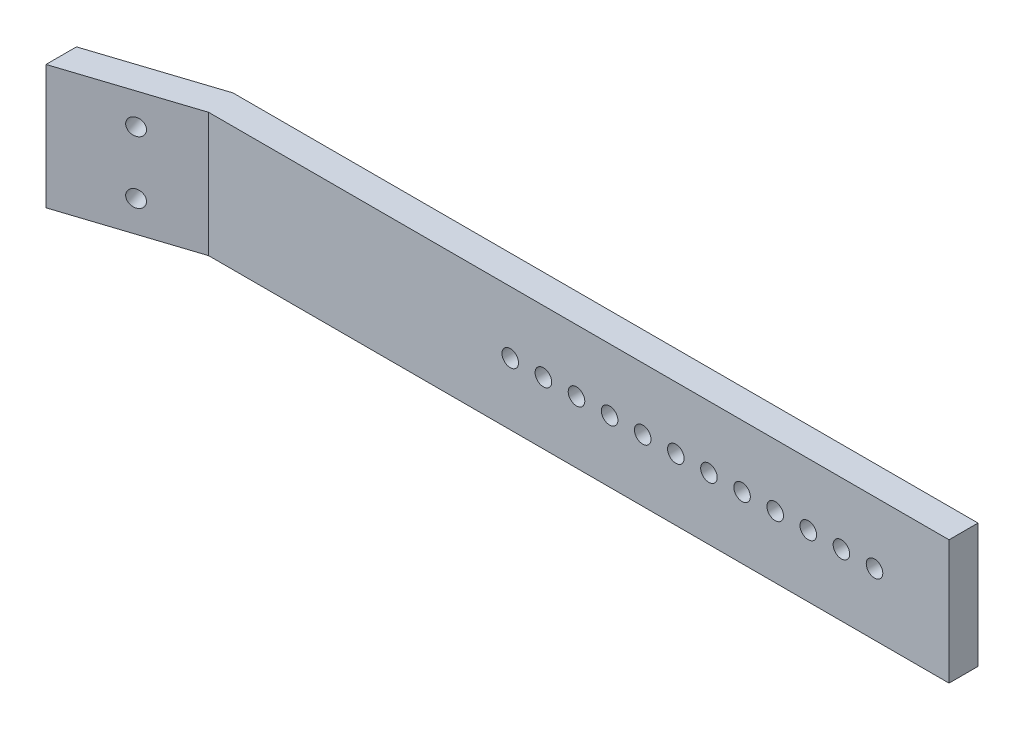
SolidWorks part; units mm, degrees
ref_plane "Front Plane" through (0, 0, 0) normal (0, 0, 1) x (1, 0, 0)
ref_plane "Top Plane" through (0, 0, 0) normal (0, 1, 0) x (1, 0, 0)
ref_plane "Right Plane" through (0, 0, 0) normal (1, 0, 0) x (0, 0, -1)
sketch "Sketch1" plane through (0, 0, 0) normal (0, 0, 1) x (1, 0, 0)
  line L1 (-115, 15) -> (115, 15)
  line L2 (-115, 15) -> (-115, -15)
  line L3 (-115, -15) -> (115, -15)
  line L4 (115, 15) -> (115, -15)
  line L5 (-115, 15) -> (115, -15) construction
  line L6 (-115, -15) -> (115, 15) construction
  point P0 (0, 0)
  dimension "D1" = 30
  dimension "D2" = 230
extrude "Boss-Extrude1" add sketch "Sketch1" along normal blind 50
sketch "Sketch2" plane through (0, -15, 0) normal (0, -1, 0) x (1, 0, 0)
  line L0 (-115, 9.2705) -> (-86.4683, 0)
  line L1 (-115, 50) -> (-115, 0) construction
  line L2 (-115, 0) -> (115, 0) construction
  line L3 (-115, 9.2705) -> (-115, 0)
  line L4 (-115, 0) -> (-86.4683, 0)
  dimension "D1" = 30
  dimension "D2" = 162
extrude "Cut-Extrude1" cut sketch "Sketch2" against normal blind 50
sketch "Sketch3" plane through (0, -15, 0) normal (0, -1, 0) x (1, 0, 0)
  line L1 (-86.4683, 0) -> (115, 0) construction
  line L2 (93.5317, 0) -> (93.5317, 50)
  line L3 (-115, 50) -> (115, 50) construction
  line L4 (93.5317, 50) -> (115, 50)
  line L5 (115, 50) -> (115, 0)
  line L6 (115, 0) -> (93.5317, 0)
extrude "Cut-Extrude2" cut sketch "Sketch3" against normal blind 50
sketch "Sketch4" plane through (0, -15, 0) normal (0, -1, 0) x (1, 0, 0)
  line L0 (-115, 16.6307) -> (-85.3596, 7)
  line L1 (-115, 50) -> (-115, 9.2705) construction
  line L2 (-85.3596, 7) -> (93.5317, 7)
  line L3 (93.5317, 50) -> (93.5317, 0) construction
  line L4 (-86.4683, 0) -> (-115, 9.2705) construction
  line L5 (-86.4683, 0) -> (93.5317, 0) construction
  line L6 (-115, 16.6307) -> (-115, 50)
  line L7 (-115, 50) -> (93.5317, 50)
  line L8 (93.5317, 50) -> (93.5317, 7)
  dimension "D1" = 7
  dimension "D2" = 7
extrude "Cut-Extrude3" cut sketch "Sketch4" against normal blind 50
sketch "Sketch5" plane through (-8.257, 0, -25.4124) normal (-0.309, 0, -0.9511) x (-0.9511, 0, 0.309)
  line L0 (112.2362, 15) -> (112.2362, -15) construction
  line L1 (82.2362, 15) -> (112.2362, 15) construction
  circle A0 centre (97.2362, 7.5) radius 2
  circle A1 centre (97.2362, -7.5) radius 2
  dimension "D1" = 4
  dimension "D2" = 4
  dimension "D3" = 15
  dimension "D4" = 15
  dimension "D5" = 7.5
  dimension "D6" = 15
extrude "Cut-Extrude4" cut sketch "Sketch5" against normal blind 50
sketch "Sketch6" plane through (0, 0, 0) normal (0, 0, -1) x (-1, 0, 0)
  line L0 (-93.5317, 15) -> (-93.5317, -15) construction
  circle A0 centre (-51.5317, 0) radius 2
  circle A1 centre (-59.5317, 0) radius 2
  circle A2 centre (-67.5317, 0) radius 2
  circle A3 centre (-75.5317, 0) radius 2
  circle A4 centre (-43.5317, 0) radius 2
  circle A5 centre (-35.5317, 0) radius 2
  circle A6 centre (-27.5317, 0) radius 2
  circle A7 centre (-19.5317, 0) radius 2
  circle A8 centre (-11.5317, 0) radius 2
  circle A9 centre (-3.5317, 0) radius 2
  circle A10 centre (4.4683, 0) radius 2
  circle A11 centre (12.4683, 0) radius 2
  dimension "D1" = 4
  dimension "D3" = 4
  dimension "D4" = 4
  dimension "D5" = 4
  dimension "D6" = 8
  dimension "D7" = 8
  dimension "D8" = 8
  dimension "D9" = 4
  dimension "D10" = 4
  dimension "D11" = 4
  dimension "D12" = 4
  dimension "D13" = 4
  dimension "D14" = 4
  dimension "D15" = 4
  dimension "D16" = 4
  dimension "D17" = 8
  dimension "D18" = 8
  dimension "D19" = 8
  dimension "D20" = 8
  dimension "D21" = 8
  dimension "D22" = 8
  dimension "D23" = 8
  dimension "D24" = 8
  dimension "D2" = 42
extrude "Cut-Extrude5" cut sketch "Sketch6" against normal blind 50
